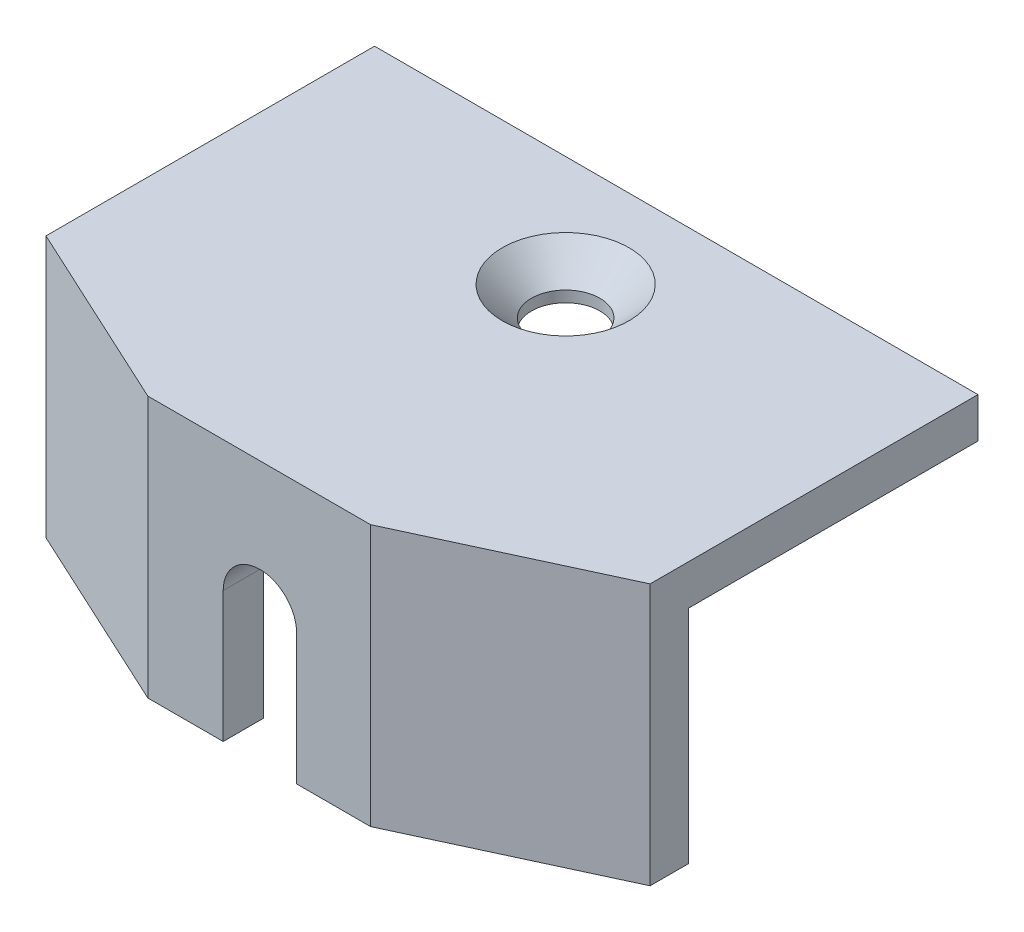
SolidWorks part; units mm, degrees
ref_plane "Front Plane" through (0, 0, 0) normal (0, 0, 1) x (1, 0, 0)
ref_plane "Top Plane" through (0, 0, 0) normal (0, 1, 0) x (1, 0, 0)
ref_plane "Right Plane" through (0, 0, 0) normal (1, 0, 0) x (0, 0, -1)
sketch "Sketch1" plane through (0, 0, 0) normal (0, 1, 0) x (1, 0, 0)
  line L2 (-15, -14.4) -> (-15, 0)
  line L3 (-15, -14.4) -> (-5.7159, -18.7)
  line L4 (-5.7159, -18.7) -> (5.7159, -18.7)
  line L5 (0, -18.7) -> (0, -23.576) construction
  line L6 (-15, 0) -> (15, 0)
  line L7 (15, -14.4) -> (5.7159, -18.7)
  line L8 (15, -14.4) -> (15, 0)
  point P1 (0, -5.5)
  point P4 (0, 0)
  point P14 (0, 0)
  dimension "D5" = 5.5
  dimension "D1" = 30
  dimension "D2" = 14.4
  dimension "D3" = 10.2315
  dimension "D4" = 11.4318
extrude "Boss-Extrude1" add sketch "Sketch1" along normal blind 2
sketch "Sketch2" plane through (0, 2, 0) normal (0, 1, 0) x (1, 0, 0)
  point P0 (0, -5.5)
  dimension "D1" = 5.5
hole_wizard "CSK for M3 Flat Head Machine Screw1" positions "Sketch2" profile "Sketch3" countersink size "M3" standard "ANSI Metric" end condition through all
sketch "Sketch3" plane through (0, 2, 5.5) normal (1, 0, 0) x (0, 0, 1)
  line L0 (0, 0) -> (0, 2)
  line L1 (0, 2) -> (1.7, 2)
  line L2 (1.7, 2) -> (1.7, 1.45)
  line L3 (1.7, 1.45) -> (3.15, 0)
  line L5 (3.15, 0) -> (0, 0)
  line L6 (-1.7, 1.45) -> (-3.15, 0) construction
  line L11 (0, -6.35) -> (0, 107.95) construction
  dimension "Thru Hole Dia." = 3.4
  dimension "Thru Hole Depth" = 2
  dimension "Near C'Sink Dia." = 6.3
  dimension "Near C'Sink Angle" = 90
sketch "Sketch4" plane through (0, 2, 0) normal (0, 1, 0) x (1, 0, 0)
  line L0 (-15, -14.4) -> (-15, -16.3337)
  line L1 (-15, -16.3337) -> (-5.5728, -20.7)
  line L2 (-5.5728, -20.7) -> (5.5, -20.7)
  line L3 (5.5, -20.7) -> (15, -16.3)
  line L4 (15, -16.3) -> (15, -14.4)
  line L5 (15, -14.4) -> (5.7159, -18.7)
  line L6 (5.7159, -18.7) -> (-5.7159, -18.7)
  line L7 (-5.7159, -18.7) -> (-15, -14.4)
  dimension "D1" = 2
extrude "Boss-Extrude2" add sketch "Sketch4" against normal blind 13
sketch "Sketch5" plane through (0, 0, 20.7) normal (0, 0, 1) x (1, 0, 0)
  line L0 (-5.5728, -11) -> (5.5, -11) construction
  line L1 (0, -4.5) -> (0, -11) construction
  line L2 (1.825, -4.5) -> (1.825, -11)
  line L3 (-1.825, -4.5) -> (-1.825, -11)
  circle A0 centre (0, -4.5) radius 1.825 construction
  arc A1 (1.825, -4.5) -> (-1.825, -4.5) centre (0, -4.5) ccw
  arc A2 (-1.825, -11) -> (1.825, -11) centre (0, -11) ccw
  point P0 (0, -4.5)
  point P5 (0, -7.75)
  dimension "D2" = 3.65
  dimension "D1" = 6.5
extrude "Cut-Extrude1" cut sketch "Sketch5" against normal blind 7
